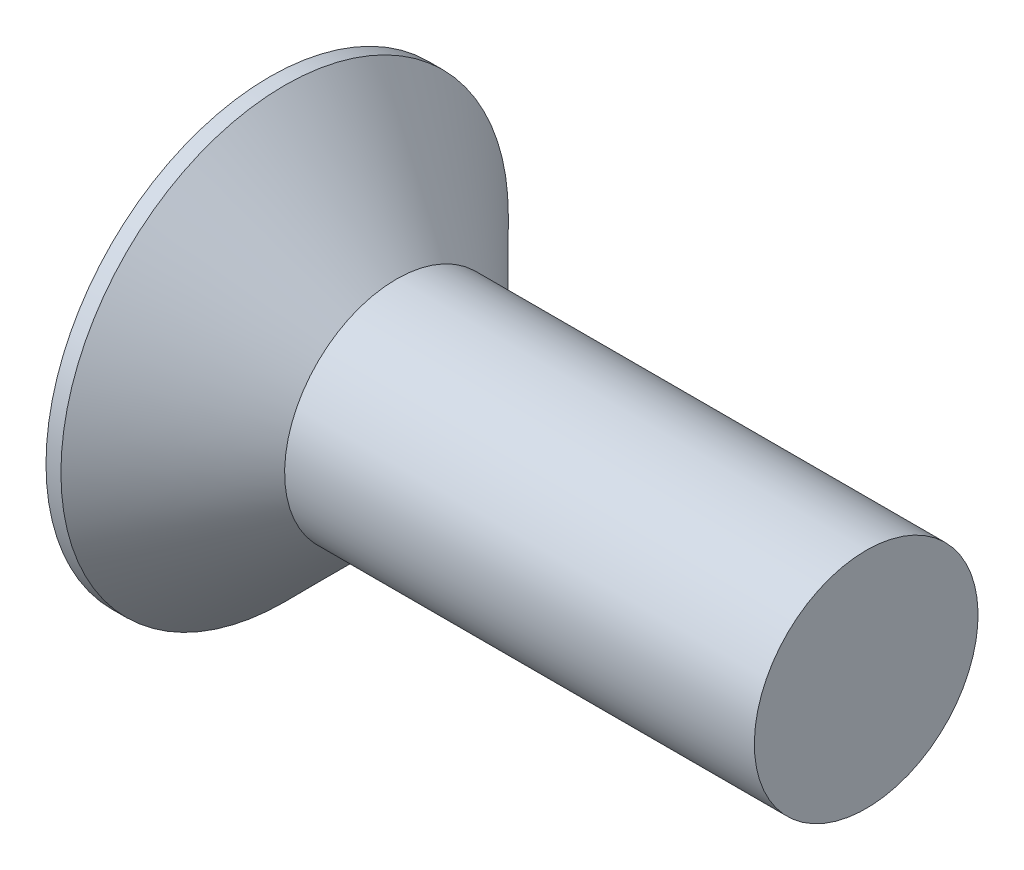
SolidWorks part; units mm, degrees
ref_plane "Přední" through (0, 0, 0) normal (0, 0, 1) x (1, 0, 0)
ref_plane "Horní" through (0, 0, 0) normal (0, 1, 0) x (1, 0, 0)
ref_plane "Pravá" through (0, 0, 0) normal (1, 0, 0) x (0, 0, -1)
sketch "Skica1" plane through (0, 0, 0) normal (0, 0, 1) x (1, 0, 0)
  line L0 (0, 0) -> (0, -3)
  line L1 (0, -3) -> (0.2, -3)
  line L2 (1.7, -1.5) -> (8, -1.5)
  line L3 (8, -1.5) -> (8, 0)
  line L4 (8, 0) -> (0, 0)
  line L5 (0, 0) -> (-8, 0) construction
  line L6 (0.2, -3) -> (1.7, -1.5)
  dimension "D1" = 3
  dimension "D2" = 6
  dimension "D3" = 1.7
  dimension "D4" = 45
  dimension "D5" = 8
revolve "Rotovat1" add sketch "Skica1" angle 360 about L5
